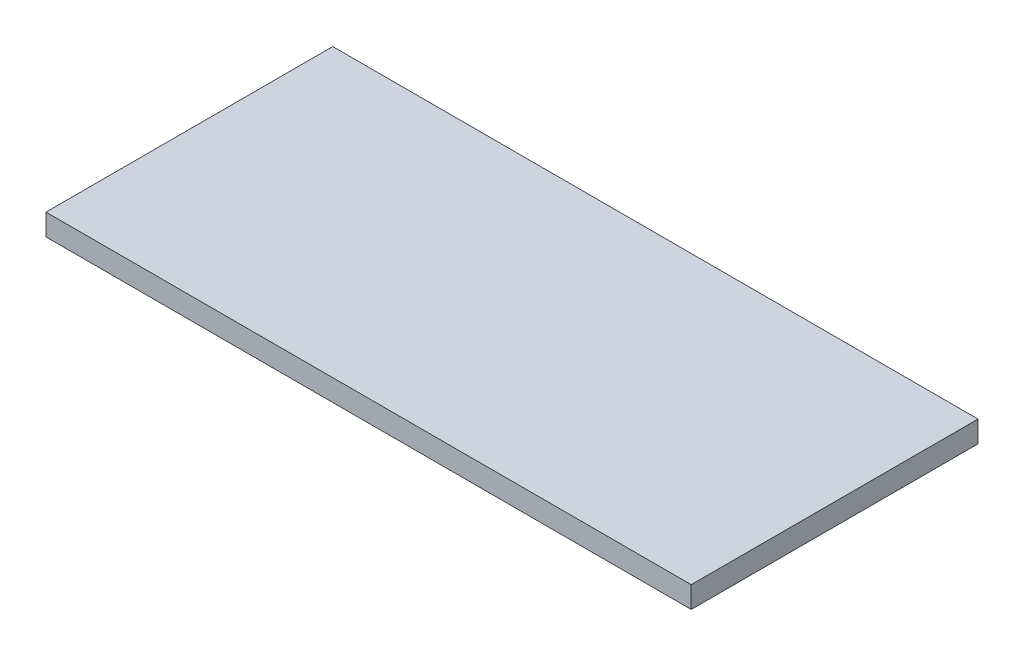
SolidWorks part; units mm, degrees
material "Pinho"
ref_plane "Plano frontal" through (0, 0, 0) normal (0, 0, 1) x (1, 0, 0)
ref_plane "Plano superior" through (0, 0, 0) normal (0, 1, 0) x (1, 0, 0)
ref_plane "Plano direito" through (0, 0, 0) normal (1, 0, 0) x (0, 0, -1)
sketch "Esboço1" plane through (0, 0, 0) normal (0, 1, 0) x (1, 0, 0)
  line L1 (-225, -100) -> (225, -100)
  line L2 (-225, -100) -> (-225, 100)
  line L3 (-225, 100) -> (225, 100)
  line L4 (225, -100) -> (225, 100)
  line L5 (-225, -100) -> (225, 100) construction
  line L6 (-225, 100) -> (225, -100) construction
  point P0 (0, 0)
  dimension "D1" = 450
  dimension "D2" = 200
extrude "Ressalto-extrusão1" add sketch "Esboço1" along normal blind 15
